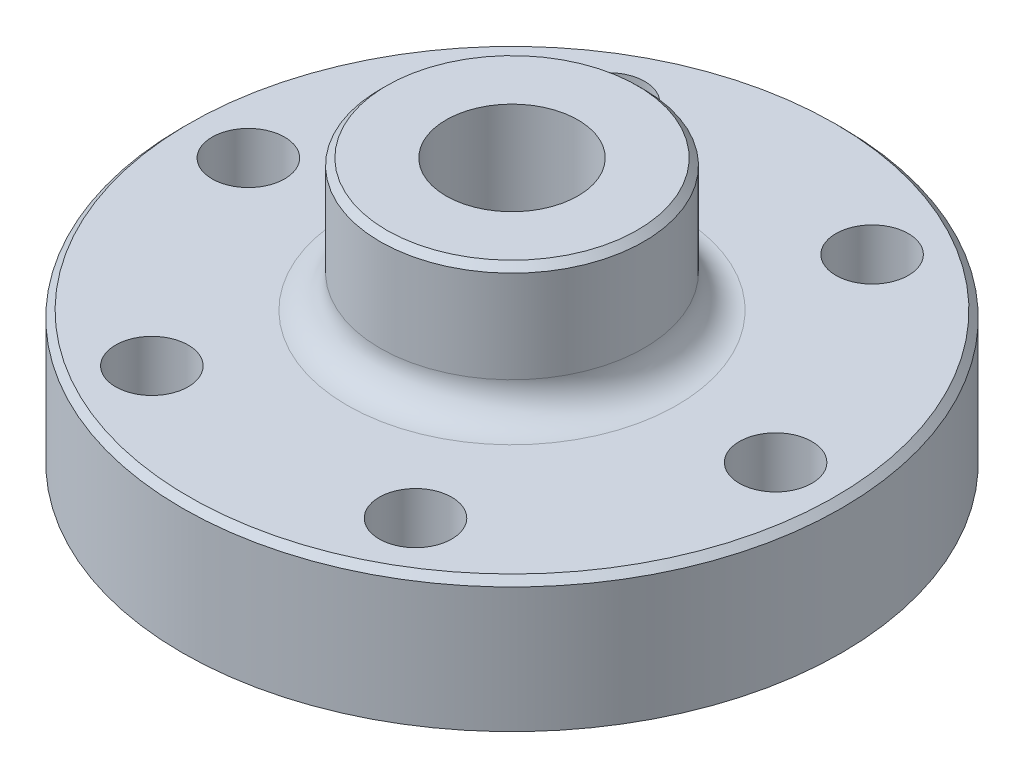
SolidWorks part; units mm, degrees
ref_plane "前视基准面" through (0, 0, 0) normal (0, 0, 1) x (1, 0, 0)
ref_plane "上视基准面" through (0, 0, 0) normal (0, 1, 0) x (1, 0, 0)
ref_plane "右视基准面" through (0, 0, 0) normal (1, 0, 0) x (0, 0, -1)
sketch "草图2" plane through (0, 0, 0) normal (0, 1, 0) x (1, 0, 0)
  line L0 (-75.18, 0) -> (44.1874, 0) construction
  line L2 (0, 73.0247) -> (0, -100.8175) construction
  circle A0 centre (0, 0) radius 1270
  point P2 (470.4267, 234.8898)
  point P3 (51.3345, 107.882)
  point P6 (0, 0)
extrude "凸台-拉伸1" add sketch "草图2" along normal blind 571.5 contours A0
sketch "草图3" plane through (0, 0, 0) normal (0, 0, 1) x (1, 0, 0)
  line L0 (-1270, 0) -> (1270, 0) construction
  line L5 (-1270, 63.5) -> (-762, 63.5)
  line L6 (-1270, 63.5) -> (-1270, 0)
  line L7 (-1270, 0) -> (-762, 0)
  line L8 (-762, 63.5) -> (-762, 0)
  line L10 (0, 0) -> (0, -1225.1672) construction
revolve "切除-旋转1" cut sketch "草图3" angle 360 about L10
chamfer "倒角2" distance 25.4 angle 45 1 edges at (0, 571.5, 1270)
sketch "草图4" plane through (0, 0, 0) normal (0, 1, 0) x (1, 0, 0)
  circle A0 centre (-507.7394, 879.4304) radius 139.7
  circle A1 centre (507.7394, 879.4304) radius 139.7
  circle A2 centre (1015.4788, 0) radius 139.7
  circle A3 centre (507.7394, -879.4304) radius 139.7
  circle A4 centre (-507.7394, -879.4304) radius 139.7
  circle A5 centre (-1015.4788, 0) radius 139.7
  circle A6 centre (0, 0) radius 1015.4788 construction
  point P19 (0, 0)
  dimension "D1" = 6
extrude "切除-拉伸1" cut sketch "草图4" along normal blind 1016
ref_plane "基准面4" through (0, 574.04, 0) normal (0, 1, 0) x (1, 0, 0)
sketch "草图5" plane through (0, 574.04, 0) normal (0, 1, 0) x (1, 0, 0)
  circle A0 centre (0, 0) radius 508
extrude "凸台-拉伸2" add sketch "草图5" along normal blind 508 from surface at -2.54 starting at face at (-1015.4788, 571.5, 139.7)
fillet "圆角10" radius 127 1 edges at (0, 571.5, 508)
chamfer "倒角3" distance 25.4 angle 45 1 edges at (0, 1079.5, 508)
sketch "草图6" plane through (0, 574.04, 0) normal (0, 1, 0) x (1, 0, 0)
  circle A0 centre (0, 0) radius 254
extrude "切除-拉伸2" cut sketch "草图6" against normal through all both and the other way through all
